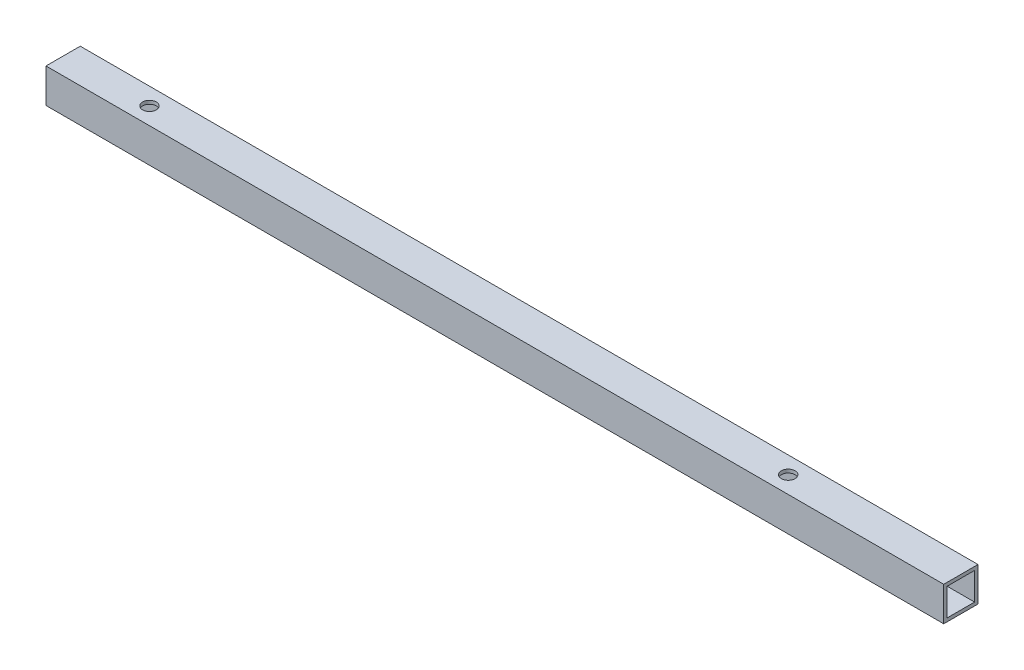
SolidWorks part; units mm, degrees
material "Brass"
ref_plane "Front Plane" through (0, 0, 0) normal (0, 0, 1) x (1, 0, 0)
ref_plane "Top Plane" through (0, 0, 0) normal (0, 1, 0) x (1, 0, 0)
ref_plane "Right Plane" through (0, 0, 0) normal (1, 0, 0) x (0, 0, -1)
sketch "Sketch1" plane through (0, 0, 0) normal (1, 0, 0) x (0, 0, -1)
  line L1 (-1.9844, 1.9844) -> (1.9844, 1.9844)
  line L2 (-1.9844, 1.9844) -> (-1.9844, -1.9844)
  line L3 (-1.9844, -1.9844) -> (1.9844, -1.9844)
  line L4 (1.9844, 1.9844) -> (1.9844, -1.9844)
  line L5 (-1.9844, 1.9844) -> (1.9844, -1.9844) construction
  line L6 (-1.9844, -1.9844) -> (1.9844, 1.9844) construction
  point P0 (0, 0)
  dimension "D1" = 3.9688
  dimension "D2" = 3.9688
extrude "Boss-Extrude1" add sketch "Sketch1" along normal blind 104
sketch "Sketch2" plane through (0, 0, 0) normal (-1, 0, 0) x (0, 0, 1)
  line L1 (-1.5875, 1.5875) -> (1.5875, 1.5875)
  line L2 (-1.5875, 1.5875) -> (-1.5875, -1.5875)
  line L3 (-1.5875, -1.5875) -> (1.5875, -1.5875)
  line L4 (1.5875, 1.5875) -> (1.5875, -1.5875)
  line L5 (-1.5875, 1.5875) -> (1.5875, -1.5875) construction
  line L6 (-1.5875, -1.5875) -> (1.5875, 1.5875) construction
  point P0 (0, 0)
  dimension "D1" = 3.175
  dimension "D2" = 3.175
extrude "Cut-Extrude1" cut sketch "Sketch2" against normal through all
sketch "Sketch3" plane through (0, 1.9844, 0) normal (0, 1, 0) x (1, 0, 0)
  line L0 (0, 1.9844) -> (0, -1.9844) construction
  circle A0 centre (10, 0) radius 0.7937
  dimension "D2" = 1.5875
  dimension "D1" = 10
extrude "Cut-Extrude2" cut sketch "Sketch3" against normal through all
sketch "Sketch4" plane through (0, 1.9844, 0) normal (0, 1, 0) x (1, 0, 0)
  line L0 (104, 1.9844) -> (104, -1.9844) construction
  circle A0 centre (84, 0) radius 0.7937
  point P2 (104, 0)
  dimension "D2" = 1.5875
  dimension "D1" = 20
extrude "Cut-Extrude3" cut sketch "Sketch4" against normal through all
